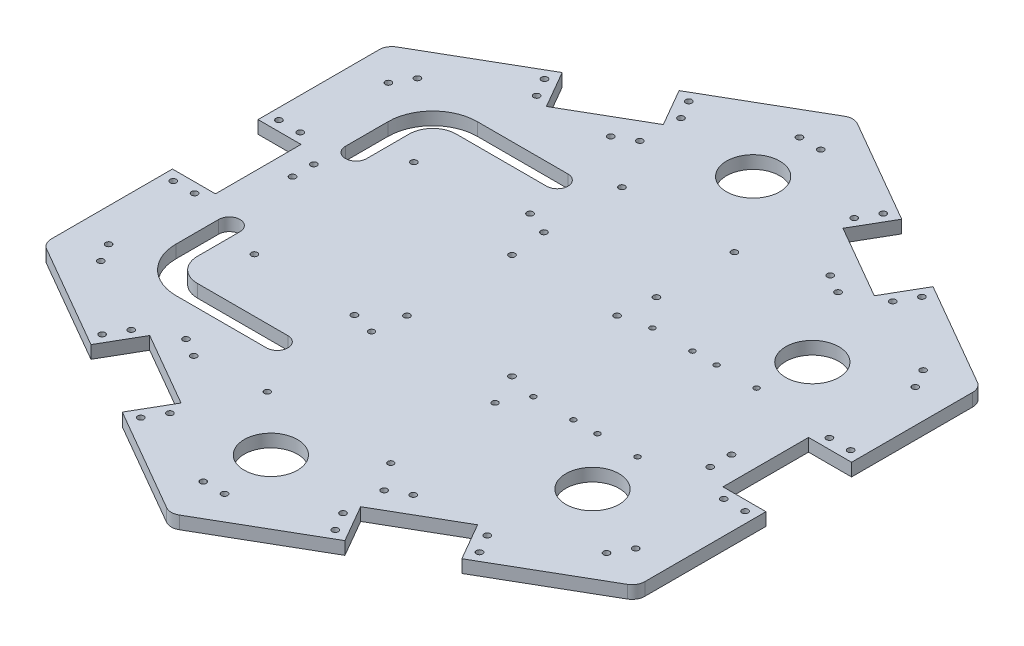
SolidWorks part; units mm, degrees
ref_plane "Face" through (0, 0, 0) normal (0, 0, 1) x (1, 0, 0)
ref_plane "Dessus" through (0, 0, 0) normal (0, 1, 0) x (1, 0, 0)
ref_plane "Droite" through (0, 0, 0) normal (1, 0, 0) x (0, 0, -1)
sketch "Sketch1" plane through (0, 0, 0) normal (0, 1, 0) x (1, 0, 0)
  line L4 (-139.3679, 20.1) -> (-119.1679, 20.1)
  line L8 (0, 0) -> (-153.3131, 0) construction
  line L9 (-121.2436, 70) -> (-139.3679, 38.6077) construction
  line L10 (0, 0) -> (-153.3131, -88.5154) construction
  line L11 (0, 0) -> (-153.3131, 88.5154) construction
  line L12 (-153.3131, 88.5154) -> (-153.3131, -88.5154) construction
  line L13 (-138.5641, 80) -> (0, 0)
  line L15 (-139.3679, 20.1) -> (-139.3679, 77)
  line L17 (-119.1679, 20.1) -> (-119.1679, -20.1)
  line L19 (-121.2436, -70) -> (-139.3679, -38.6077) construction
  line L20 (-139.3679, -20.1) -> (-139.3679, -77)
  line L21 (-138.5641, -80) -> (0, 0)
  line L22 (-139.3679, -20.1) -> (-119.1679, -20.1)
  arc A0 (-139.3679, 77) -> (-138.5641, 80) centre (-133.3679, 77) cw
  circle A2 centre (-123.7436, 65.6699) radius 1.45
  circle A3 centre (-123.7436, -65.6699) radius 1.45
  arc A4 (-139.3679, -77) -> (-138.5641, -80) centre (-133.3679, -77) ccw
  point P1 (-144.6528, -83.5154)
  point P4 (0, 0)
  dimension "D5" = 6
  dimension "D7" = 2.9
  dimension "D1" = 30
  dimension "D2" = 20.2
  dimension "D3" = 160
  dimension "D4" = 40.2
  dimension "D6" = 20
  dimension "D8" = 5
extrude "Boss-Extrude2" add sketch "Sketch1" along normal mid plane 6
sketch "Sketch2" plane through (0, 3, 0) normal (0, 1, 0) x (1, 0, 0)
  line L0 (-129.2679, 20.1) -> (-129.2679, -20.1) construction
  line L3 (-119.1679, 0) -> (-129.2679, 0) construction
  line L7 (-139.3679, 20.1) -> (-119.1679, 20.1) construction
  line L8 (-119.1679, -20.1) -> (-139.3679, -20.1) construction
  line L9 (-119.1679, 20.1) -> (-119.1679, -20.1) construction
  circle A0 centre (-134.2679, 24.8) radius 1.45
  circle A1 centre (-124.2679, 24.8) radius 1.45
  circle A2 centre (-124.2679, -24.8) radius 1.45
  circle A3 centre (-134.2679, -24.8) radius 1.45
  circle A4 centre (-108.0679, 15) radius 1.45
  circle A5 centre (-108.0679, 5) radius 1.45
  point P10 (0, 0)
  point P12 (0, 0)
  dimension "D1" = 2.9
  dimension "D6" = 2.9
  dimension "D8" = 10
  dimension "D5" = 5.1
  dimension "D2" = 5
  dimension "D3" = 4.7
  dimension "D4" = 11.1
  dimension "D7" = 2
extrude "Cut-Extrude1" cut sketch "Sketch2" against normal through all
pattern_circular "CirPattern7" count 6 over 360 about axis through (0, 0, 0) along (0, 1, 0) of "Boss-Extrude2", "Cut-Extrude1"
sketch "Sketch3" plane through (0, 3, 0) normal (0, 1, 0) x (1, 0, 0)
  line L0 (0, -55) -> (0, 55) construction
  line L1 (-55, 0) -> (55, 0) construction
  circle A0 centre (-24.675, 24.675) radius 1.45
  circle A1 centre (24.675, 24.675) radius 1.45
  circle A2 centre (24.675, -24.675) radius 1.45
  circle A3 centre (-24.675, -24.675) radius 1.45
  point P13 (0, 0)
  point P16 (-55.4218, 11.4886)
  dimension "D1" = 2.9
  dimension "D2" = 24.675
  dimension "D3" = 24.675
extrude "Cut-Extrude2" cut sketch "Sketch3" against normal through all
sketch "Sketch4" plane through (0, 3, 0) normal (0, 1, 0) x (1, 0, 0)
  line L0 (38, 27.95) -> (56.8, 27.95) construction
  line L1 (56.8, 27.95) -> (68.1, 27.95) construction
  line L2 (68.1, 27.95) -> (86.9, 27.95) construction
  line L3 (-55, 0) -> (55, 0) construction
  circle A0 centre (38, 27.95) radius 1.25
  circle A1 centre (56.8, 27.95) radius 1.25
  circle A2 centre (68.1, 27.95) radius 1.25
  circle A3 centre (86.9, 27.95) radius 1.25
  circle A4 centre (86.9, -27.95) radius 1.25
  circle A5 centre (68.1, -27.95) radius 1.25
  circle A6 centre (56.8, -27.95) radius 1.25
  circle A7 centre (38, -27.95) radius 1.25
  dimension "D1" = 2.5
  dimension "D2" = 2.5
  dimension "D3" = 18.8
  dimension "D4" = 38
  dimension "D5" = 27.95
  dimension "D7" = 11.3
  dimension "D6" = 2
extrude "Cut-Extrude3" cut sketch "Sketch4" against normal through all
sketch "Sketch5" plane through (0, 3, 0) normal (0, 1, 0) x (1, 0, 0)
  circle A0 centre (-85.46, -35.53) radius 1.45
  circle A1 centre (-85.46, 39.35) radius 1.45
  circle A2 centre (-37.24, 45.71) radius 1.45
  circle A3 centre (-37.24, -36.76) radius 1.45
  dimension "D1" = 2.9
  dimension "D2" = 2.9
  dimension "D3" = 2.9
  dimension "D4" = 2.9
extrude "Cut-Extrude4" cut sketch "Sketch5" against normal through all
sketch "Sketch6" plane through (0, 3, 0) normal (0, 1, 0) x (1, 0, 0)
  circle A0 centre (-26.5, -39.45) radius 1.375
  circle A1 centre (31.5, -39.45) radius 1.375
  circle A2 centre (31.5, -88.45) radius 1.375
  circle A3 centre (-26.5, -88.45) radius 1.375
  dimension "D1" = 2.75
  dimension "D2" = 2.75
  dimension "D3" = 2.75
  dimension "D4" = 2.75
sketch "Sketch7" plane through (0, 3, 0) normal (0, 1, 0) x (1, 0, 0)
  circle A0 centre (-26.415, 78.025) radius 1.45
  circle A1 centre (26.415, 78.025) radius 1.45
  circle A2 centre (26.415, 41.395) radius 1.45
  circle A3 centre (-26.415, 41.395) radius 1.45
  dimension "D1" = 2.9
  dimension "D2" = 2.9
  dimension "D3" = 2.9
  dimension "D4" = 2.9
extrude "Cut-Extrude5" cut sketch "Sketch6" against normal through all
extrude "Cut-Extrude6" cut sketch "Sketch7" against normal through all
sketch "Sketch9" plane through (0, 3, 0) normal (0, 1, 0) x (1, 0, 0)
  line L0 (-108, -29.76) -> (-108, -49.76)
  line L1 (-87, -70.76) -> (-44.5, -70.76)
  line L2 (-44.5, -60.76) -> (-87, -60.76)
  line L3 (-98, -49.76) -> (-98, -29.76)
  line L6 (-67, -50.76) -> (-47.1, -50.76) construction
  line L7 (119.1679, -20.1) -> (76.9911, -93.1524) construction
  line L8 (0, 0) -> (98.0795, -56.6262) construction
  line L9 (-14.08, 0) -> (14.08, 0) construction
  line L10 (-98, 49.76) -> (-98, 29.76)
  line L11 (-44.5, 60.76) -> (-87, 60.76)
  line L12 (-87, 70.76) -> (-44.5, 70.76)
  line L13 (-108, 29.76) -> (-108, 49.76)
  circle A2 centre (89.4192, -51.6262) radius 12.5
  arc A3 (-108, -49.76) -> (-87, -70.76) centre (-87, -49.76) ccw
  arc A4 (-44.5, -70.76) -> (-44.5, -60.76) centre (-44.5, -65.76) ccw
  arc A5 (-87, -60.76) -> (-98, -49.76) centre (-87, -49.76) cw
  arc A6 (-98, -29.76) -> (-108, -29.76) centre (-103, -29.76) ccw
  arc A7 (-88, -49.76) -> (-87, -50.76) centre (-87, -49.76) ccw construction
  circle A8 centre (89.4192, 51.6262) radius 12.5
  arc A9 (-87, 60.76) -> (-98, 49.76) centre (-87, 49.76) ccw
  arc A10 (-44.5, 70.76) -> (-44.5, 60.76) centre (-44.5, 65.76) cw
  arc A11 (-108, 49.76) -> (-87, 70.76) centre (-87, 49.76) cw
  arc A12 (-98, 29.76) -> (-108, 29.76) centre (-103, 29.76) cw
  point P14 (86.1868, -49.76)
  point P21 (86.9604, -49.76)
  point P22 (83.6553, -48.2984)
  point P23 (89.7628, -51.8246)
  dimension "D1" = 10
  dimension "D3" = 25
  dimension "D4" = 10
  dimension "D5" = 10
  dimension "D6" = 20
  dimension "D7" = 42.5
extrude "Cut-Extrude7" cut sketch "Sketch9" against normal through all
sketch "Sketch10" plane through (0, 3, 0) normal (0, 1, 0) x (1, 0, 0)
  line L0 (0, 0) -> (0, -113.2524) construction
  line L1 (42.1768, -113.2524) -> (-42.1768, -113.2524) construction
  line L2 (-14.08, 0) -> (14.08, 0) construction
  circle A0 centre (0, -113.2524) radius 12.5
  circle A1 centre (0, 113.2524) radius 12.5
  point P8 (0, 0)
  dimension "D1" = 25
extrude "Cut-Extrude8" cut sketch "Sketch10" against normal through all
